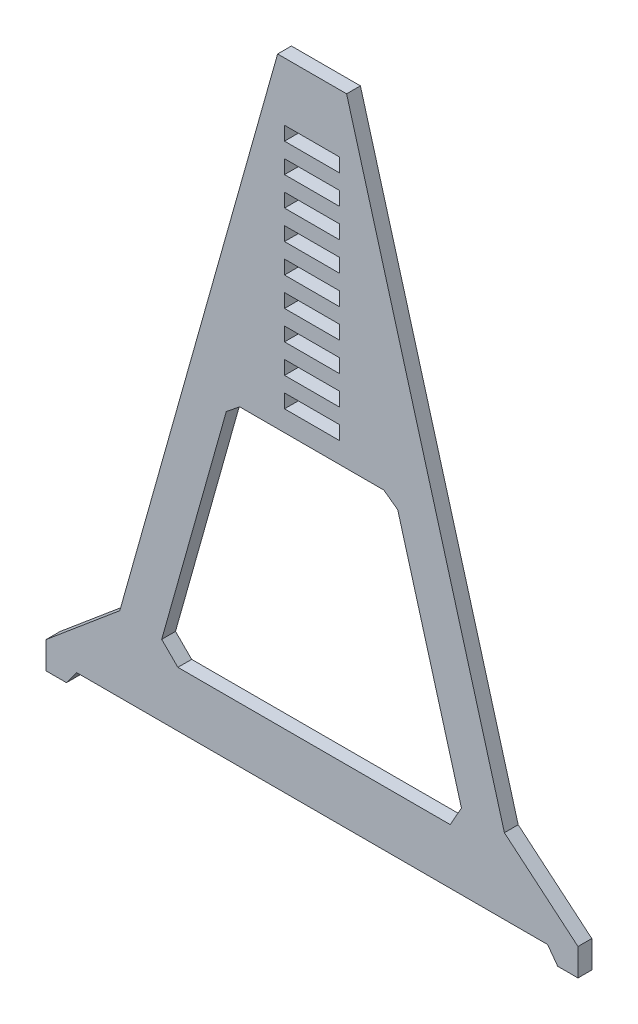
SolidWorks part; units mm, degrees
ref_plane "Front Plane" through (0, 0, 0) normal (0, 0, 1) x (1, 0, 0)
ref_plane "Top Plane" through (0, 0, 0) normal (0, 1, 0) x (1, 0, 0)
ref_plane "Right Plane" through (0, 0, 0) normal (1, 0, 0) x (0, 0, -1)
sketch "Sketch1" plane through (0, 0, 0) normal (0, 0, 1) x (1, 0, 0)
  line L0 (0, 597.4769) -> (0, 0)
  line L1 (452.1892, -599.186) -> (469.8386, -599.186)
  line L13 (353.9957, -435.2947) -> (63.5, 597.4769)
  line L14 (0, 0) -> (152.4, 0)
  line L15 (152.4, 0) -> (285.2154, -472.186)
  line L16 (489.4572, -548.9603) -> (361.7106, -441.7683)
  line L17 (361.7106, -441.7683) -> (361.7106, -424.1556)
  line L18 (489.4572, -548.9603) -> (489.4572, -599.186)
  line L19 (489.4572, -599.186) -> (469.8386, -599.186)
  line L20 (361.7106, -441.7683) -> (353.9957, -435.2947)
  line L21 (0, -472.186) -> (0, -573.786)
  line L22 (0, -472.186) -> (285.2154, -472.186)
  line L23 (285.2154, -472.186) -> (0, -472.186) construction
  line L24 (63.5, 597.4769) -> (0, 597.4769)
  line L25 (0, -573.786) -> (0, 1182.2052) construction
  line L26 (0, -573.786) -> (415.9763, -573.786)
  line L27 (452.1892, -599.186) -> (433.5746, -573.786)
  line L28 (433.5746, -573.786) -> (415.9763, -573.786)
  point P0 (0, 0)
  dimension "D1" = 152.4
  dimension "D2" = 76.2
  dimension "D3" = 127
  dimension "D4" = 63.5
  dimension "D5" = 25.4
  dimension "D6" = 1196.6629
  dimension "D7" = 599.186
  dimension "D8" = 40
  dimension "D9" = 489.4572
extrude "Boss-Extrude1" add sketch "Sketch1" along normal blind 25.4 contours L13 L24 L0 L14 L15 L22 L21 L1 L19 L18 L16 L20
mirror "Mirror1" about plane through (0, 0, 25.4) normal (1, 0, 0) of "Boss-Extrude1"
chamfer "Chamfer1" distance 38.1 angle 45 2 edges at (285.2154, -472.186, 12.7) (-285.2154, -472.186, 12.7)
chamfer "Chamfer2" distance 20.32 angle 36 2 edges at (152.4, 0, 12.7) (-152.4, 0, 12.7)
sketch "Sketch2" plane through (0, 0, 25.4) normal (0, 0, 1) x (1, 0, 0)
  line L0 (0, 0) -> (0, 38.1)
  line L1 (-133.1246, 0) -> (132.08, 0) construction
  line L2 (-50.8, 38.1) -> (50.8, 38.1)
  line L3 (-50.8, 38.1) -> (-50.8, 63.5)
  line L4 (-50.8, 63.5) -> (50.8, 63.5)
  line L5 (50.8, 38.1) -> (50.8, 63.5)
  line L6 (-50.8, 91.44) -> (-50.8, 116.84)
  line L7 (-50.8, 91.44) -> (50.8, 91.44)
  line L8 (0, 63.5) -> (0, 657.8492)
  line L9 (50.8, 91.44) -> (50.8, 116.84)
  line L10 (-50.8, 116.84) -> (50.8, 116.84)
  line L11 (-50.8, 144.78) -> (-50.8, 170.18)
  line L12 (-50.8, 144.78) -> (50.8, 144.78)
  line L13 (50.8, 144.78) -> (50.8, 170.18)
  line L14 (-50.8, 170.18) -> (50.8, 170.18)
  line L15 (-50.8, 198.12) -> (-50.8, 223.52)
  line L16 (-50.8, 198.12) -> (50.8, 198.12)
  line L17 (50.8, 198.12) -> (50.8, 223.52)
  line L18 (-50.8, 223.52) -> (50.8, 223.52)
  line L19 (-50.8, 251.46) -> (-50.8, 276.86)
  line L20 (-50.8, 251.46) -> (50.8, 251.46)
  line L21 (50.8, 251.46) -> (50.8, 276.86)
  line L22 (-50.8, 276.86) -> (50.8, 276.86)
  line L23 (-50.8, 304.8) -> (-50.8, 330.2)
  line L24 (-50.8, 304.8) -> (50.8, 304.8)
  line L25 (50.8, 304.8) -> (50.8, 330.2)
  line L26 (-50.8, 330.2) -> (50.8, 330.2)
  line L27 (-50.8, 358.14) -> (-50.8, 383.54)
  line L28 (-50.8, 358.14) -> (50.8, 358.14)
  line L29 (50.8, 358.14) -> (50.8, 383.54)
  line L30 (-50.8, 383.54) -> (50.8, 383.54)
  line L31 (452.1892, -599.186) -> (489.4572, -599.186) construction
  line L32 (-50.8, 411.48) -> (-50.8, 436.88)
  line L33 (-50.8, 436.88) -> (50.8, 436.88)
  line L34 (50.8, 411.48) -> (50.8, 436.88)
  line L35 (-50.8, 411.48) -> (50.8, 411.48)
  line L36 (-50.8, 464.82) -> (-50.8, 490.22)
  line L37 (-50.8, 490.22) -> (50.8, 490.22)
  line L38 (50.8, 464.82) -> (50.8, 490.22)
  line L39 (-50.8, 464.82) -> (50.8, 464.82)
  point P3 (0, 50.8)
  dimension "D1" = 25.4
  dimension "D2" = 38.1
  dimension "D3" = 101.6
  dimension "D5" = 637.286
  dimension "D6" = 27.94
  dimension "D8" = 27.94
  dimension "D4" = 7
  dimension "D7" = 3
extrude "Cut-Extrude2" cut sketch "Sketch2" against normal through all contours L30 L27 L28 L8 | L30 L8 L28 L29 | L26 L8 L24 L25 | L10 L6 L7 L8 | L10 L8 L7 L9 | L22 L21 L20 L19 | L18 L17 L16 L15 | L14 L13 L12 L11 | L4 L5 L2 L3
pattern_linear "LPattern1" count 2 spacing 106.68 along (0, 1, 0) of "Cut-Extrude2"
